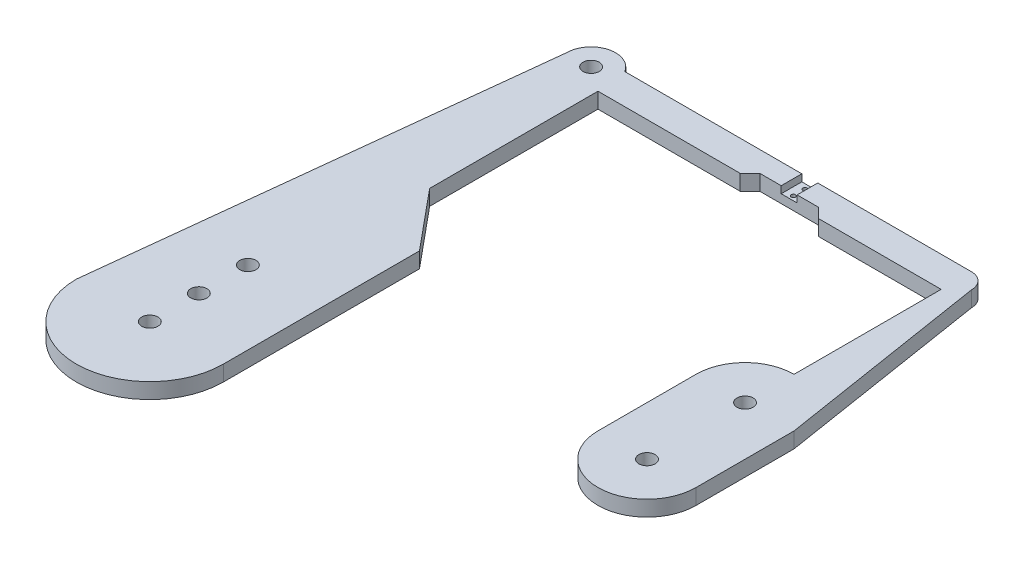
SolidWorks part; units mm, degrees
ref_plane "Front Plane" through (0, 0, 0) normal (0, 0, 1) x (1, 0, 0)
ref_plane "Top Plane" through (0, 0, 0) normal (0, 1, 0) x (1, 0, 0)
ref_plane "Right Plane" through (0, 0, 0) normal (1, 0, 0) x (0, 0, -1)
sketch "Sketch1" plane through (0, 0, 0) normal (0, 1, 0) x (1, 0, 0)
  line L0 (10, -7.2) -> (10, -75.8579)
  line L1 (150, -7.2) -> (150, -67.2)
  line L2 (30, -180) -> (30, -100)
  line L3 (30, -100) -> (10, -75.8579)
  line L4 (75, 5.2158) -> (8.532, 5.2158)
  line L5 (72, -3.2) -> (84, -3.2)
  line L6 (59, -7.2) -> (10, -7.2)
  line L8 (84, -3.2) -> (96, -3.2)
  line L9 (75, 5.2158) -> (150, 5.2158)
  line L10 (72, -3.2) -> (68, -7.2)
  line L11 (156.3437, -1.1279) -> (170, -87.2)
  line L12 (-10, 0) -> (-30, -180)
  line L13 (170, -87.2) -> (170, -127.2)
  line L14 (130, -87.2) -> (130, -127.2)
  line L15 (68, -7.2) -> (59, -7.2)
  line L16 (96, -3.2) -> (100, -7.2)
  line L17 (100, -7.2) -> (150, -7.2)
  circle A0 centre (0, 0) radius 3.3
  arc A1 (8.532, 5.2158) -> (-10, 0) centre (0, 0) ccw
  circle A2 centre (0, -180) radius 3.3
  arc A3 (-30, -180) -> (30, -180) centre (0, -180) ccw
  arc A4 (156.3437, -1.1279) -> (150, 5.2158) centre (150, -1.1279) ccw
  arc A5 (150, -67.2) -> (130, -87.2) centre (150, -87.2) ccw
  circle A6 centre (150, -87.2) radius 3.3
  arc A7 (130, -127.2) -> (170, -127.2) centre (150, -127.2) ccw
  circle A8 centre (84, -1.5) radius 0.889
  circle A9 centre (84, 3.216) radius 0.889
  circle A10 centre (150, -127.2) radius 3.3
  circle A11 centre (0, -160) radius 3.3
  circle A12 centre (0, -140) radius 3.3
extrude "Boss-Extrude1" add sketch "Sketch1" along normal blind 6.35
sketch "Sketch2" plane through (0, 0, 0) normal (0, -1, 0) x (1, 0, 0)
  line L1 (87.25, 1.5) -> (87.25, 4.8858)
  line L3 (80.75, 1.5) -> (80.75, 4.8858)
  line L4 (80.75, 1.5) -> (80.75, -5.8382)
  line L5 (80.75, -5.8382) -> (87.25, -5.8382)
  line L6 (87.25, -5.8382) -> (87.25, 1.5)
  line L7 (80.75, 4.8858) -> (87.25, 4.8858)
sketch "Sketch3" plane through (0, 6.35, 0) normal (0, 1, 0) x (1, 0, 0)
  line L0 (80.75, 5.8382) -> (80.75, -4.8858)
  line L1 (80.75, -4.8858) -> (87.25, -4.8858)
  line L2 (87.25, -4.8858) -> (87.25, 5.8382)
  line L3 (87.25, 5.8382) -> (80.75, 5.8382)
extrude "Cut-Extrude2" cut sketch "Sketch3" against normal blind 2.85
